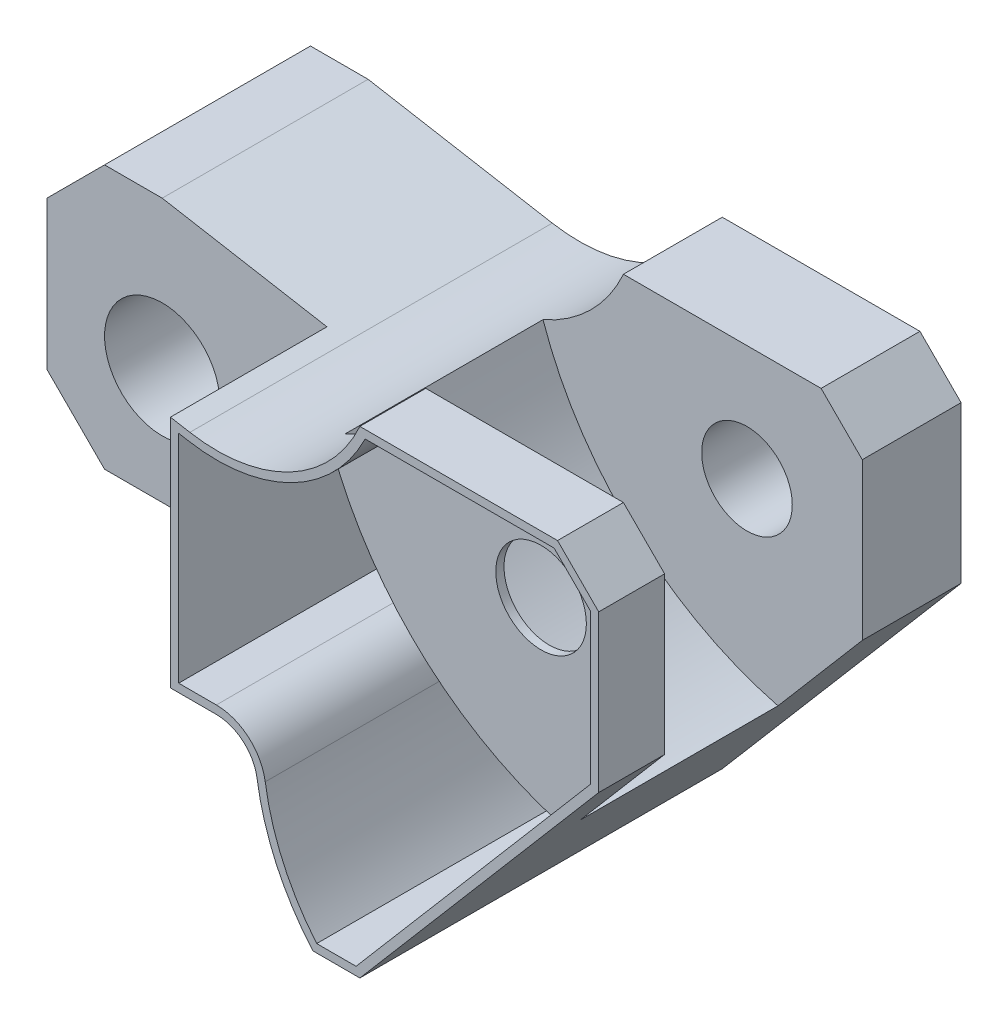
SolidWorks part; units mm, degrees
material "AISI 1020"
ref_plane "Front Plane" through (0, 0, 0) normal (0, 0, 1) x (1, 0, 0)
ref_plane "Top Plane" through (0, 0, 0) normal (0, 1, 0) x (1, 0, 0)
ref_plane "Right Plane" through (0, 0, 0) normal (1, 0, 0) x (0, 0, -1)
sketch "Sketch1" plane through (0, 0, 0) normal (0, 0, 1) x (1, 0, 0)
  line L0 (0, 0) -> (0, 27275.3694) construction
  line L1 (0, 0) -> (27275.3694, 0) construction
  line L2 (-14, 11) -> (-14, -7)
  line L3 (-14, -7) -> (-7, -14)
  line L4 (-7, -14) -> (25.5755, -14)
  line L5 (37.297, -33) -> (43, -33)
  line L6 (43, -33) -> (72, 1)
  line L7 (72, 1) -> (72, 20)
  line L9 (67, 25) -> (43, 25)
  line L10 (22.3614, 14.0571) -> (0, 18)
  line L11 (0, 18) -> (-7, 18)
  line L12 (-7, 18) -> (-14, 11)
  line L13 (72, 30.2408) -> (72, 47.2269) construction
  line L14 (-14, -7) -> (-14, -19.315) construction
  line L15 (-14, 11) -> (-14, 31.7841) construction
  line L16 (-4.6035, 18) -> (4.6872, 18) construction
  line L17 (67, 25) -> (72, 20)
  arc A0 (25.5755, -14) -> (30.5212, -18.2647) centre (25.5755, -19) cw
  arc A1 (30.5212, -18.2647) -> (37.297, -33) centre (59.2059, -14) ccw
  arc A2 (43, 25) -> (22.3614, 14.0571) centre (25.6607, 32.7684) cw
  circle A3 centre (0, 0) radius 7
  point P17 (67, 30.2408)
  point P20 (0, 0)
  dimension "D7" = 5
  dimension "D8" = 29
  dimension "D12" = 10
  dimension "D17" = 19
  dimension "D18" = 14
  dimension "D2" = 86
  dimension "D3" = 29
  dimension "D4" = 24
  dimension "D5" = 19
  dimension "D6" = 19
  dimension "D9" = 45
  dimension "D10" = 45
  dimension "D11" = 45
  dimension "D13" = 14
  dimension "D14" = 32
  dimension "D15" = 7
  dimension "D16" = 7
  dimension "D19" = 14
  dimension "D20" = 14
  dimension "D21" = 29
  dimension "D22" = 58
  dimension "D23" = 5
extrude "Boss-Extrude1" add sketch "Sketch1" along normal mid plane 44
sketch "Sketch3" plane through (0, 0, 0) normal (0, 0, 1) x (1, 0, 0)
  line L0 (72, 1) -> (72, 20) construction
  line L1 (72, 20) -> (67, 25) construction
  line L2 (67, 25) -> (43, 25) construction
  line L3 (72, 1) -> (72, 20)
  line L4 (72, 20) -> (67, 25)
  line L5 (67, 25) -> (43, 25)
  line L6 (43, -33) -> (72, 1) construction
  line L7 (61.7647, -11) -> (72, 1)
  arc A0 (22.3614, 14.0571) -> (43, 25) centre (25.6607, 32.7684) ccw construction
  arc A1 (33.2369, 15.3443) -> (43, 25) centre (25.6607, 32.7684) ccw
  arc A2 (33.2369, 15.3443) -> (61.7647, -11) centre (72, 28.7019) ccw
  point P10 (61.7647, -11)
  point P11 (29.8545, 14.237)
  point P12 (0, 0)
  dimension "D2" = 41
  dimension "D1" = 36
extrude "Cut-Extrude1" cut sketch "Sketch3" against normal blind 24 from offset 14
sketch "Sketch5" plane through (0, 0, 22) normal (0, 0, 1) x (1, 0, 0)
  line L0 (20, 14.4735) -> (20, -14)
  line L11 (72, 20) -> (67, 25)
  line L12 (67, 25) -> (43, 25)
  line L13 (22.3614, 14.0571) -> (0, 18)
  line L14 (0, 18) -> (-7, 18)
  line L15 (-7, 18) -> (-14, 11)
  line L16 (-14, 11) -> (-14, -7)
  line L17 (-14, -7) -> (-7, -14)
  line L18 (-7, -14) -> (25.5755, -14)
  line L19 (37.297, -33) -> (43, -33)
  line L20 (43, -33) -> (72, 1)
  line L21 (72, 1) -> (72, 20)
  line L24 (20, 14.4735) -> (0, 18)
  line L25 (0, 18) -> (-7, 18)
  line L26 (-7, 18) -> (-14, 11)
  line L27 (-14, 11) -> (-14, -7)
  line L28 (-14, -7) -> (-7, -14)
  line L29 (-7, -14) -> (20, -14)
  line L32 (72, 1) -> (72, 20)
  arc A3 (22.3614, 14.0571) -> (43, 25) centre (25.6607, 32.7684) ccw
  arc A4 (30.5212, -18.2647) -> (25.5755, -14) centre (25.5755, -19) ccw
  arc A5 (30.5212, -18.2647) -> (37.297, -33) centre (59.2059, -14) ccw
  line M19 (22.3614, 14.0571) -> (0, 18)
  line M20 (0, 18) -> (-7, 18)
  line M21 (-7, 18) -> (-14, 11)
  line M22 (-14, 11) -> (-14, -7)
  line M23 (-14, -7) -> (-7, -14)
  line M24 (-7, -14) -> (25.5755, -14)
  circle M30 centre (0, 0) radius 7
  dimension "D2" = 52
  dimension "D1" = 0
extrude "Cut-Extrude2" cut sketch "Sketch5" against normal blind 19 contours L0 M19 M20 M21 M22 M23 M24 M30
sketch "Sketch6" plane through (0, 0, 22) normal (0, 0, 1) x (1, 0, 0)
  line L0 (67, 25) -> (43, 25) construction
  line L1 (72, 1) -> (72, 20) construction
  circle A0 centre (58, 11) radius 5.5
  dimension "D1" = 11
  dimension "D2" = 14
  dimension "D3" = 14
extrude "Cut-Extrude3" cut sketch "Sketch6" against normal through all
sketch "Sketch7" plane through (0, 0, 22) normal (0, 0, 1) x (1, 0, 0)
  line L16 (22.1877, 13.0723) -> (21, 13.2817)
  line L17 (21, 13.2817) -> (21, -13)
  line L18 (21, -13) -> (25.5755, -13)
  line L19 (37.7583, -32) -> (42.5386, -32)
  line L20 (42.5386, -32) -> (71, 1.3685)
  line L21 (71, 1.3685) -> (71, 19.5858)
  line L22 (71, 19.5858) -> (66.5858, 24)
  line L23 (66.5858, 24) -> (43.6361, 24)
  line L24 (22.1877, 13.0723) -> (21, 13.2817)
  line L25 (21, 13.2817) -> (21, -13)
  line L26 (21, -13) -> (25.5755, -13)
  line L27 (37.7583, -32) -> (42.5386, -32)
  line L28 (42.5386, -32) -> (71, 1.3685)
  line L29 (71, 1.3685) -> (71, 19.5858)
  line L30 (71, 19.5858) -> (66.5858, 24)
  line L31 (66.5858, 24) -> (43.6361, 24)
  arc A6 (31.5103, -18.1176) -> (25.5755, -13) centre (25.5755, -19) ccw
  arc A7 (31.5103, -18.1176) -> (37.7583, -32) centre (59.2059, -14) ccw
  arc A8 (22.1877, 13.0723) -> (43.6361, 24) centre (25.6607, 32.7684) ccw
  arc A9 (31.5103, -18.1176) -> (25.5755, -13) centre (25.5755, -19) ccw
  arc A10 (31.5103, -18.1176) -> (37.7583, -32) centre (59.2059, -14) ccw
  arc A11 (22.1877, 13.0723) -> (43.6361, 24) centre (25.6607, 32.7684) ccw
  dimension "D1" = 1
extrude "Cut-Extrude4" cut sketch "Sketch7" against normal offset from surface (7 mm away) 1 up to face at (63.5, 11, 14)
sketch "Sketch8" plane through (0, 0, 15) normal (0, 0, 1) x (1, 0, 0)
  line L0 (42.5386, -32) -> (71, 1.3685) construction
  line L1 (37.7583, -32) -> (42.5386, -32) construction
  line L2 (21, -13) -> (25.5755, -13) construction
  line L3 (21, 13.2817) -> (21, -13) construction
  line L4 (42.5386, -32) -> (59.9868, -11.5434)
  line L5 (37.7583, -32) -> (42.5386, -32)
  line L6 (21, -13) -> (25.5755, -13)
  line L7 (21, 13.2817) -> (21, -13)
  line L8 (22.1877, 13.0723) -> (21, 13.2817) construction
  line L9 (22.1877, 13.0723) -> (21, 13.2817)
  arc A1 (31.5103, -18.1176) -> (37.7583, -32) centre (59.2059, -14) ccw construction
  arc A2 (32.2915, 15.0185) -> (61.5151, -11.9683) centre (72, 28.7019) ccw
  arc A3 (32.6467, 14.0282) -> (59.9868, -11.5434) centre (72, 28.7019) ccw
  arc A4 (31.5103, -18.1176) -> (25.5755, -13) centre (25.5755, -19) ccw construction
  arc A5 (22.1877, 13.0723) -> (43.6361, 24) centre (25.6607, 32.7684) ccw construction
  arc A6 (31.5103, -18.1176) -> (37.7583, -32) centre (59.2059, -14) ccw
  arc A7 (31.5103, -18.1176) -> (25.5755, -13) centre (25.5755, -19) ccw
  arc A8 (22.1877, 13.0723) -> (32.6467, 14.0282) centre (25.6607, 32.7684) ccw
  point P13 (0, 0)
  dimension "D1" = 1
extrude "Cut-Extrude5" cut sketch "Sketch8" against normal up to surface (25 mm away) up to face at (63.5, 11, -10)
equation "\"A\" = 84"
equation "\"B\" = 59"
equation "\"C\"= 45"
